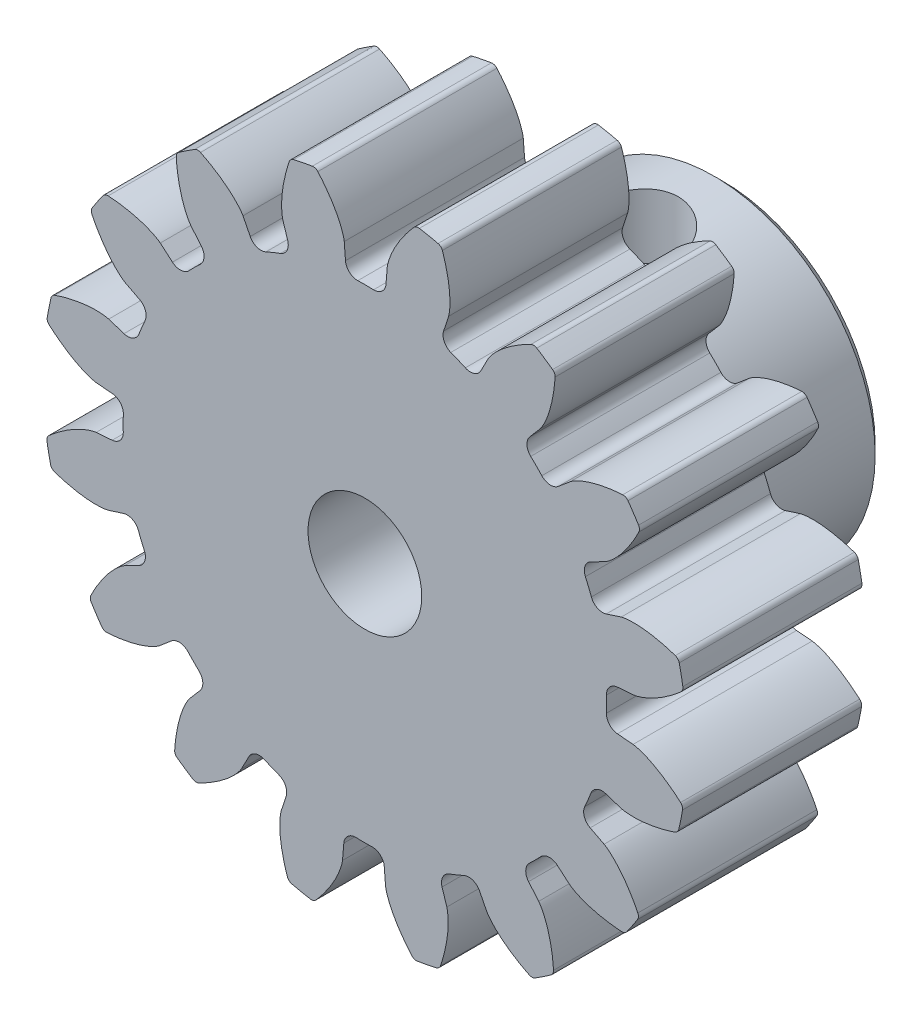
SolidWorks part; units mm, degrees
ref_plane "Front Plane" through (0, 0, 0) normal (0, 0, 1) x (1, 0, 0)
ref_plane "Top Plane" through (0, 0, 0) normal (0, 1, 0) x (1, 0, 0)
ref_plane "Right Plane" through (0, 0, 0) normal (1, 0, 0) x (0, 0, -1)
sketch "Sketch1" plane through (0, 0, 0) normal (0, 0, 1) x (1, 0, 0)
  circle A0 centre (0, 0) radius 9
  dimension "D1" = 18
extrude "Boss-Extrude1" add sketch "Sketch1" along normal blind 5
sketch "Sketch2" plane through (0, 0, 0) normal (0, 0, 1) x (1, 0, 0)
  line L0 (0, 0) -> (22.2244, 0) construction
  line L1 (0, 0) -> (6.7302, 0.5169) construction
  line L2 (0, 0) -> (6.7266, -0.5614) construction
  line L5 (0, 0) -> (0, -27.429) construction
  line L6 (6.7302, 0.5169) -> (7.5037, 0.5764) construction
  line L7 (6.7266, -0.5614) -> (7.4898, -0.6251) construction
  circle A0 centre (0, 0) radius 7.5175 construction
  circle A1 centre (0, 0) radius 9 construction
  circle A2 centre (0, 0) radius 8 construction
  arc A5 (6.7266, -0.5614) -> (6.7302, 0.5169) centre (0, 0) ccw construction
  spline S0 degree 4 poles (7.4898, -0.6251) (7.493, -0.6254) (7.5019, -0.6265) (7.5187, -0.6291) (7.5459, -0.6342) (7.5804, -0.642) (7.6247, -0.6536) (7.6765, -0.6692) (7.7329, -0.6882) (7.7938, -0.711) (7.854, -0.7357) (7.9135, -0.762) (7.9723, -0.7897) (8.043, -0.8251) (8.1268, -0.87) (8.2234, -0.9261) (8.3313, -0.9939) (8.4393, -1.0674) (8.5439, -1.1434) (8.6476, -1.2242) (8.7465, -1.3053) (8.847, -1.3936) (8.9387, -1.4772) (9.0388, -1.5753) (9.1189, -1.6557) (9.2216, -1.7664) (9.2814, -1.8331) (9.3504, -1.9128) (9.3805, -1.9489) (9.399, -1.9712) knots 0 0 0 0 0 0.005377 0.015084 0.028532 0.04661 0.064855 0.092111 0.119476 0.146842 0.174209 0.201575 0.228941 0.256307 0.307035 0.361767 0.4165 0.471232 0.525964 0.580697 0.635429 0.690161 0.744894 0.799626 0.854358 0.909091 0.954545 1 1 1 1 1 construction
  spline S1 degree 4 poles (7.4898, -0.6251) (7.493, -0.6254) (7.5019, -0.6265) (7.5187, -0.6291) (7.5459, -0.6342) (7.5804, -0.642) (7.6247, -0.6536) (7.6765, -0.6692) (7.7329, -0.6882) (7.7938, -0.711) (7.854, -0.7357) (7.9135, -0.762) (7.9723, -0.7897) (8.043, -0.8251) (8.1268, -0.87) (8.2234, -0.9261) (8.3313, -0.9939) (8.4393, -1.0674) (8.5439, -1.1434) (8.6476, -1.2242) (8.7465, -1.3053) (8.847, -1.3936) (8.9387, -1.4772) (9.0388, -1.5753) (9.1189, -1.6557) (9.1993, -1.7424) (9.2382, -1.7851) (9.2579, -1.8072) knots 0 0 0 0 0 0.005377 0.015084 0.028532 0.04661 0.064855 0.092111 0.119476 0.146842 0.174209 0.201575 0.228941 0.256307 0.307035 0.361767 0.4165 0.471232 0.525964 0.580697 0.635429 0.690161 0.744894 0.799626 0.854358 0.909091 0.909091 0.909091 0.909091 0.909091
  spline S2 degree 4 poles (7.5037, 0.5764) (7.5069, 0.5767) (7.5158, 0.5777) (7.5326, 0.5803) (7.5598, 0.5854) (7.5943, 0.5933) (7.6386, 0.6049) (7.6904, 0.6204) (7.7468, 0.6394) (7.8077, 0.6623) (7.8679, 0.6869) (7.9274, 0.7132) (7.9862, 0.7409) (8.0569, 0.7763) (8.1407, 0.8212) (8.2373, 0.8773) (8.3452, 0.9451) (8.4532, 1.0187) (8.5578, 1.0946) (8.6615, 1.1755) (8.7604, 1.2566) (8.8609, 1.3449) (8.9526, 1.4285) (9.0527, 1.5265) (9.1328, 1.6069) (9.2355, 1.7176) (9.2953, 1.7843) (9.3643, 1.864) (9.3944, 1.9002) (9.413, 1.9224) knots 0 0 0 0 0 0.005377 0.015084 0.028532 0.04661 0.064855 0.092111 0.119476 0.146842 0.174209 0.201575 0.228941 0.256307 0.307035 0.361767 0.4165 0.471232 0.525964 0.580697 0.635429 0.690161 0.744894 0.799626 0.854358 0.909091 0.954545 1 1 1 1 1 construction
  spline S3 degree 4 poles (7.5037, 0.5764) (7.5069, 0.5767) (7.5158, 0.5777) (7.5326, 0.5803) (7.5598, 0.5854) (7.5943, 0.5933) (7.6386, 0.6049) (7.6904, 0.6204) (7.7468, 0.6394) (7.8077, 0.6623) (7.8679, 0.6869) (7.9274, 0.7132) (7.9862, 0.7409) (8.0569, 0.7763) (8.1407, 0.8212) (8.2373, 0.8773) (8.3452, 0.9451) (8.4532, 1.0187) (8.5578, 1.0946) (8.6615, 1.1755) (8.7604, 1.2566) (8.8609, 1.3449) (8.9526, 1.4285) (9.0527, 1.5265) (9.1328, 1.6069) (9.2132, 1.6936) (9.2521, 1.7363) (9.2718, 1.7584) knots 0 0 0 0 0 0.005377 0.015084 0.028532 0.04661 0.064855 0.092111 0.119476 0.146842 0.174209 0.201575 0.228941 0.256307 0.307035 0.361767 0.4165 0.471232 0.525964 0.580697 0.635429 0.690161 0.744894 0.799626 0.854358 0.909091 0.909091 0.909091 0.909091 0.909091
  dimension "Base Diameter" = 15.0351
  dimension "Outside Diameter" = 18
  dimension "Pitch Diameter" = 16
  dimension "D1" = 13.5
sketch "DrLTDb" plane through (0, 0, 0) normal (0, 0, 1) x (1, 0, 0)
  line L0 (6.7266, -0.5614) -> (7.4898, -0.6251) construction
  line L1 (6.7302, 0.5169) -> (7.5037, 0.5764) construction
  line L4 (7.053, -0.5887) -> (7.4898, -0.6251)
  line L5 (7.0568, 0.542) -> (7.5037, 0.5764)
  arc A0 (6.7266, -0.5614) -> (6.7302, 0.5169) centre (0, 0) ccw construction
  circle A2 centre (0, 0) radius 9 construction
  circle A3 centre (0, 0) radius 9
  arc A4 (6.7457, -0.2423) -> (6.7471, 0.1977) centre (0, 0) ccw
  arc A5 (6.7471, 0.1977) -> (7.0568, 0.542) centre (7.0825, 0.2075) cw
  arc A6 (6.7457, -0.2423) -> (7.053, -0.5887) centre (7.0809, -0.2543) ccw
  spline S2 degree 4 poles (-89.2556, 995.8731) (5.4068, 12.6395) (6.7819, 0.6993) (7.1883, 0.5155) (7.5598, 0.5854) (7.5943, 0.5933) (7.6386, 0.6049) (7.6904, 0.6204) (7.7468, 0.6394) (7.8077, 0.6623) (7.8679, 0.6869) (7.9274, 0.7132) (7.9862, 0.7409) (8.0569, 0.7763) (8.1407, 0.8212) (8.2373, 0.8773) (8.3452, 0.9451) (8.4532, 1.0187) (8.5578, 1.0946) (8.6615, 1.1755) (8.7604, 1.2566) (8.8609, 1.3449) (8.9526, 1.4285) (9.0527, 1.5265) (9.4734, 1.9492) (10.7836, 3.5254) (-7.6996, -16.9543) (675.3164, 747.6622) knots -0.58951 -0.58951 -0.58951 -0.58951 -0.58951 0.005377 0.015084 0.028532 0.04661 0.064855 0.092111 0.119476 0.146842 0.174209 0.201575 0.228941 0.256307 0.307035 0.361767 0.4165 0.471232 0.525964 0.580697 0.635429 0.690161 0.744894 0.799626 0.854358 1.840621 1.840621 1.840621 1.840621 1.840621 only from (7.5037, 0.5764) to (9.2718, 1.7584) construction
  spline S3 degree 4 poles (-89.2695, -995.9219) (5.3929, -12.6883) (6.768, -0.748) (7.1744, -0.5642) (7.5459, -0.6342) (7.5804, -0.642) (7.6247, -0.6536) (7.6765, -0.6692) (7.7329, -0.6882) (7.7938, -0.711) (7.854, -0.7357) (7.9135, -0.762) (7.9723, -0.7897) (8.043, -0.8251) (8.1268, -0.87) (8.2234, -0.9261) (8.3313, -0.9939) (8.4393, -1.0674) (8.5439, -1.1434) (8.6476, -1.2242) (8.7465, -1.3053) (8.847, -1.3936) (8.9387, -1.4772) (9.0388, -1.5753) (9.4595, -1.9979) (10.7697, -3.5741) (-7.7135, 16.9055) (675.3025, -747.711) knots -0.58951 -0.58951 -0.58951 -0.58951 -0.58951 0.005377 0.015084 0.028532 0.04661 0.064855 0.092111 0.119476 0.146842 0.174209 0.201575 0.228941 0.256307 0.307035 0.361767 0.4165 0.471232 0.525964 0.580697 0.635429 0.690161 0.744894 0.799626 0.854358 1.840621 1.840621 1.840621 1.840621 1.840621 only from (7.4898, -0.6251) to (9.2579, -1.8072) construction
  spline S4 degree 4 poles (7.5037, 0.5764) (7.5069, 0.5767) (7.5158, 0.5777) (7.5326, 0.5803) (7.5598, 0.5854) (7.5943, 0.5933) (7.6386, 0.6049) (7.6904, 0.6204) (7.7468, 0.6394) (7.8077, 0.6623) (7.8679, 0.6869) (7.9274, 0.7132) (7.9862, 0.7409) (8.0569, 0.7763) (8.1407, 0.8212) (8.2373, 0.8773) (8.3452, 0.9451) (8.4532, 1.0187) (8.5578, 1.0946) (8.6615, 1.1755) (8.7604, 1.2566) (8.8609, 1.3449) (8.9526, 1.4285) (9.0527, 1.5265) (9.1328, 1.6069) (9.2132, 1.6936) (9.2521, 1.7363) (9.2718, 1.7584) knots 0 0 0 0 0 0.005377 0.015084 0.028532 0.04661 0.064855 0.092111 0.119476 0.146842 0.174209 0.201575 0.228941 0.256307 0.307035 0.361767 0.4165 0.471232 0.525964 0.580697 0.635429 0.690161 0.744894 0.799626 0.854358 0.909091 0.909091 0.909091 0.909091 0.909091
  spline S5 degree 4 poles (7.4898, -0.6251) (7.493, -0.6254) (7.5019, -0.6265) (7.5187, -0.6291) (7.5459, -0.6342) (7.5804, -0.642) (7.6247, -0.6536) (7.6765, -0.6692) (7.7329, -0.6882) (7.7938, -0.711) (7.854, -0.7357) (7.9135, -0.762) (7.9723, -0.7897) (8.043, -0.8251) (8.1268, -0.87) (8.2234, -0.9261) (8.3313, -0.9939) (8.4393, -1.0674) (8.5439, -1.1434) (8.6476, -1.2242) (8.7465, -1.3053) (8.847, -1.3936) (8.9387, -1.4772) (9.0388, -1.5753) (9.1189, -1.6557) (9.1993, -1.7424) (9.2382, -1.7851) (9.2579, -1.8072) knots 0 0 0 0 0 0.005377 0.015084 0.028532 0.04661 0.064855 0.092111 0.119476 0.146842 0.174209 0.201575 0.228941 0.256307 0.307035 0.361767 0.4165 0.471232 0.525964 0.580697 0.635429 0.690161 0.744894 0.799626 0.854358 0.909091 0.909091 0.909091 0.909091 0.909091
  dimension "D1" = 0.3355
extrude "Cut - DrLTDb" cut sketch "DrLTDb" along normal through all
fillet "Fillet - DrLTDb" radius 0.1678 2 edges at (8.8858, -1.4294, 2.5) (8.8942, 1.3757, 2.5)
pattern_circular "CirPattern - DrLTDb" count 16 over 360 about axis through (0, 0, 5) along (0, 0, 1) of "Cut - DrLTDb", "Fillet - DrLTDb"
sketch "DrGTDb" plane through (0, 0, 0) normal (0, 0, 1) x (1, 0, 0)
  line L0 (6.7266, -0.5614) -> (7.4898, -0.6251) construction
  line L1 (6.7302, 0.5169) -> (7.5037, 0.5764) construction
  line L2 (6.7266, -0.5614) -> (7.4898, -0.6251)
  line L3 (6.7302, 0.5169) -> (7.5037, 0.5764)
  circle A2 centre (0, 0) radius 9 construction
  circle A3 centre (0, 0) radius 7.5175 construction
  circle A4 centre (0, 0) radius 9
  circle A5 centre (0, 0) radius 7.5175
  arc A6 (7.7359, 0.6361) -> (7.5113, 0.3057) centre (7.8466, 0.3193) ccw
  arc A7 (7.7319, -0.6883) -> (7.5091, -0.3563) centre (7.8442, -0.3722) cw
  spline S0 degree 4 poles (-89.2695, -995.9219) (5.3929, -12.6883) (6.768, -0.748) (7.1744, -0.5642) (7.5459, -0.6342) (7.5804, -0.642) (7.6247, -0.6536) (7.6765, -0.6692) (7.7329, -0.6882) (7.7938, -0.711) (7.854, -0.7357) (7.9135, -0.762) (7.9723, -0.7897) (8.043, -0.8251) (8.1268, -0.87) (8.2234, -0.9261) (8.3313, -0.9939) (8.4393, -1.0674) (8.5439, -1.1434) (8.6476, -1.2242) (8.7465, -1.3053) (8.847, -1.3936) (8.9387, -1.4772) (9.0388, -1.5753) (9.4595, -1.9979) (10.7697, -3.5741) (-7.7135, 16.9055) (675.3025, -747.711) knots -0.58951 -0.58951 -0.58951 -0.58951 -0.58951 0.005377 0.015084 0.028532 0.04661 0.064855 0.092111 0.119476 0.146842 0.174209 0.201575 0.228941 0.256307 0.307035 0.361767 0.4165 0.471232 0.525964 0.580697 0.635429 0.690161 0.744894 0.799626 0.854358 1.840621 1.840621 1.840621 1.840621 1.840621 only from (7.4898, -0.6251) to (9.2579, -1.8072) construction
  spline S2 degree 4 poles (-89.2556, 995.8731) (5.4068, 12.6395) (6.7819, 0.6993) (7.1883, 0.5155) (7.5598, 0.5854) (7.5943, 0.5933) (7.6386, 0.6049) (7.6904, 0.6204) (7.7468, 0.6394) (7.8077, 0.6623) (7.8679, 0.6869) (7.9274, 0.7132) (7.9862, 0.7409) (8.0569, 0.7763) (8.1407, 0.8212) (8.2373, 0.8773) (8.3452, 0.9451) (8.4532, 1.0187) (8.5578, 1.0946) (8.6615, 1.1755) (8.7604, 1.2566) (8.8609, 1.3449) (8.9526, 1.4285) (9.0527, 1.5265) (9.4734, 1.9492) (10.7836, 3.5254) (-7.6996, -16.9543) (675.3164, 747.6622) knots -0.58951 -0.58951 -0.58951 -0.58951 -0.58951 0.005377 0.015084 0.028532 0.04661 0.064855 0.092111 0.119476 0.146842 0.174209 0.201575 0.228941 0.256307 0.307035 0.361767 0.4165 0.471232 0.525964 0.580697 0.635429 0.690161 0.744894 0.799626 0.854358 1.840621 1.840621 1.840621 1.840621 1.840621 only from (7.5037, 0.5764) to (9.2718, 1.7584) construction
  spline S3 degree 4 poles (7.4898, -0.6251) (7.493, -0.6254) (7.5019, -0.6265) (7.5187, -0.6291) (7.5459, -0.6342) (7.5804, -0.642) (7.6247, -0.6536) (7.6765, -0.6692) (7.7329, -0.6882) (7.7938, -0.711) (7.854, -0.7357) (7.9135, -0.762) (7.9723, -0.7897) (8.043, -0.8251) (8.1268, -0.87) (8.2234, -0.9261) (8.3313, -0.9939) (8.4393, -1.0674) (8.5439, -1.1434) (8.6476, -1.2242) (8.7465, -1.3053) (8.847, -1.3936) (8.9387, -1.4772) (9.0388, -1.5753) (9.1189, -1.6557) (9.1993, -1.7424) (9.2382, -1.7851) (9.2579, -1.8072) knots 0 0 0 0 0 0.005377 0.015084 0.028532 0.04661 0.064855 0.092111 0.119476 0.146842 0.174209 0.201575 0.228941 0.256307 0.307035 0.361767 0.4165 0.471232 0.525964 0.580697 0.635429 0.690161 0.744894 0.799626 0.854358 0.909091 0.909091 0.909091 0.909091 0.909091
  spline S4 degree 4 poles (7.5037, 0.5764) (7.5069, 0.5767) (7.5158, 0.5777) (7.5326, 0.5803) (7.5598, 0.5854) (7.5943, 0.5933) (7.6386, 0.6049) (7.6904, 0.6204) (7.7468, 0.6394) (7.8077, 0.6623) (7.8679, 0.6869) (7.9274, 0.7132) (7.9862, 0.7409) (8.0569, 0.7763) (8.1407, 0.8212) (8.2373, 0.8773) (8.3452, 0.9451) (8.4532, 1.0187) (8.5578, 1.0946) (8.6615, 1.1755) (8.7604, 1.2566) (8.8609, 1.3449) (8.9526, 1.4285) (9.0527, 1.5265) (9.1328, 1.6069) (9.2132, 1.6936) (9.2521, 1.7363) (9.2718, 1.7584) knots 0 0 0 0 0 0.005377 0.015084 0.028532 0.04661 0.064855 0.092111 0.119476 0.146842 0.174209 0.201575 0.228941 0.256307 0.307035 0.361767 0.4165 0.471232 0.525964 0.580697 0.635429 0.690161 0.744894 0.799626 0.854358 0.909091 0.909091 0.909091 0.909091 0.909091
  dimension "D1" = 0.3355
extrude "Cut-DrGTDb" [suppressed] cut sketch "DrGTDb" along normal through all
fillet "Fillet - DrGTDb" [suppressed] radius 0.1678
pattern_circular "CirPattern - DrGTDb" [suppressed] count 16 over 360
sketch "Sketch4" plane through (0, 0, 0) normal (0, 0, 1) x (1, 0, 0)
  circle A0 centre (0, 0) radius 4.5
  dimension "D1" = 9
extrude "Boss-Extrude2" add sketch "Sketch4" against normal blind 5
sketch "Sketch3" plane through (0, 0, 0) normal (0, 0, 1) x (1, 0, 0)
  circle A0 centre (0, 0) radius 1.5875
  dimension "D1" = 3.175
extrude "Cut-Extrude1" cut sketch "Sketch3" along normal through all both and the other way through all
sketch "Sketch5" plane through (0, 0, 0) normal (0, 1, 0) x (1, 0, 0)
  circle A0 centre (0, 2.5) radius 1.25
  dimension "D1" = 2.5
  dimension "D2" = 2.5
extrude "Cut-Extrude2" cut sketch "Sketch5" along normal through all
cosmetic thread "Cosmetic Thread1" parameters "D2"=3
chamfer "Chamfer1" distance 0.25 angle 45 2 edges at (4.5, 0, -5) (4.5, 0, 0)
equation "\"Module\"= 1"
equation "\"Teeth Number\"= 16"
equation "\"Pressure Angle\"= 20"
equation "\"Pitch Diameter\"= \"Module\" * \"Teeth Number\""
equation "\"Outside Diameter\"= \"Pitch Diameter\" + 2 * \"Module\""
equation "\"Base Diameter\"= \"Pitch Diameter\" * cos ( \"Pressure Angle\" )"
equation "\"Root Diameter\"= \"Pitch Diameter\" - 2.5 * \"Module\""
equation "\"Addendum\"= \"Module\""
equation "\"Dedendum\"= 1.25 * \"Module\""
equation "\"D1@Sketch1\"=\"Outside Diameter\""
equation "\"Base Diameter@Sketch2\" = \"Base Diameter\""
equation "\"Outside Diameter@Sketch2\" = \"Outside Diameter\""
equation "\"Pitch Diameter@Sketch2\"=\"Pitch Diameter\""
equation "\"Clearance\"= \"Dedendum\" - \"Addendum\""
equation "\"Fillet Radius\"= \"Clearance\" * cos ( \"Pressure Angle\" ) * tan ( ( 90 + \"Pressure Angle\" ) / 2 )"
equation "\"Alpha\"= sqr ( ( \"Pitch Diameter\" ^ 2 - \"Base Diameter\" ^ 2 ) ) / \"Base Diameter\" * 180 / PI - \"Pressure Angle\""
equation "\"Beta\"= 360 / ( 4 * \"Teeth Number\" ) - \"Alpha\""
equation "\"Phi\"= sqr ( ( ( \"Outside Diameter\" / 2 ) ^ 2 ) - ( ( \"Base Diameter\" / 2 ) ^ 2 ) ) / ( \"Base Diameter\" / 2 )"
equation "\"D1@DrLTDb\" = \"Fillet Radius\""
equation "\"D1@Fillet - DrLTDb\" = \"Fillet Radius\" / 2"
equation "\"D1@CirPattern - DrLTDb\" = \"Teeth Number\""
equation "\"DrLTDb\"= IIF (  ( \"Root Diameter\" +  ( 2 * \"Fillet Radius\" )  )  > \"Base Diameter\" ,  suppressed  ,  unsuppressed  ) "
equation "\"D1@Sketch2\"=\"Root Diameter\""
equation "\"D1@Fillet - DrGTDb\" = \"Fillet Radius\" / 2"
equation "\"D1@CirPattern - DrGTDb\" = \"Teeth Number\""
equation "\"D1@Fillet - DrGTDb\"=\"Fillet Radius\"/2"
equation "\"Cut - DrLTDb\"= IIF ( ( \"Root Diameter\" + ( 2 * \"Fillet Radius\" ) ) > \"Base Diameter\" , \"suppressed\" , \"unsuppressed\" )"
equation "\"Cut-DrGTDb\"= IIF ( ( \"Root Diameter\" + ( 2 * \"Fillet Radius\" ) ) > \"Base Diameter\" , \"unsuppressed\" , \"suppressed\" )"
equation "\"Fillet - DrLTDb\"= IIF ( ( \"Root Diameter\" + ( 2 * \"Fillet Radius\" ) ) > \"Base Diameter\" , \"suppressed\" , \"unsuppressed\" )"
equation "\"Fillet - DrGTDb\"= IIF ( ( \"Root Diameter\" + ( 2 * \"Fillet Radius\" ) ) > \"Base Diameter\" , \"unsuppressed\" , \"suppressed\" )"
equation "\"CirPattern - DrLTDb\"= IIF ( ( \"Root Diameter\" + ( 2 * \"Fillet Radius\" ) ) > \"Base Diameter\" , \"suppressed\" , \"unsuppressed\" )"
equation "\"CirPattern - DrGTDb\"= IIF ( ( \"Root Diameter\" + ( 2 * \"Fillet Radius\" ) ) > \"Base Diameter\" , \"unsuppressed\" , \"suppressed\" )"
equation "\"D1@DrGTDb\"=\"Fillet Radius\""
